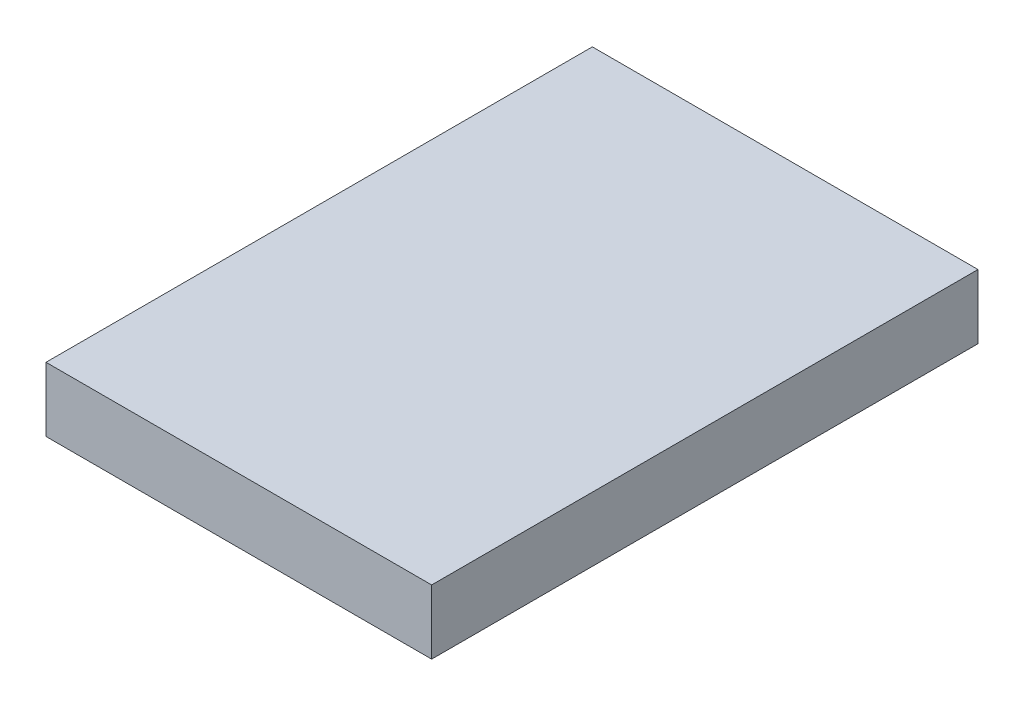
SolidWorks part; units mm, degrees
material "ABS"
ref_plane "Front Plane" through (0, 0, 0) normal (0, 0, 1) x (1, 0, 0)
ref_plane "Top Plane" through (0, 0, 0) normal (0, 1, 0) x (1, 0, 0)
ref_plane "Right Plane" through (0, 0, 0) normal (1, 0, 0) x (0, 0, -1)
sketch "Sketch1" plane through (0, 0, 0) normal (0, 0, 1) x (1, 0, 0)
  line L1 (-30, 5) -> (30, 5)
  line L2 (-30, 5) -> (-30, -5)
  line L3 (-30, -5) -> (30, -5)
  line L4 (30, 5) -> (30, -5)
  line L5 (-30, 5) -> (30, -5) construction
  line L6 (-30, -5) -> (30, 5) construction
  point P0 (0, 0)
  dimension "D1" = 60
  dimension "D2" = 10
extrude "Boss-Extrude1" add sketch "Sketch1" along normal blind 85
